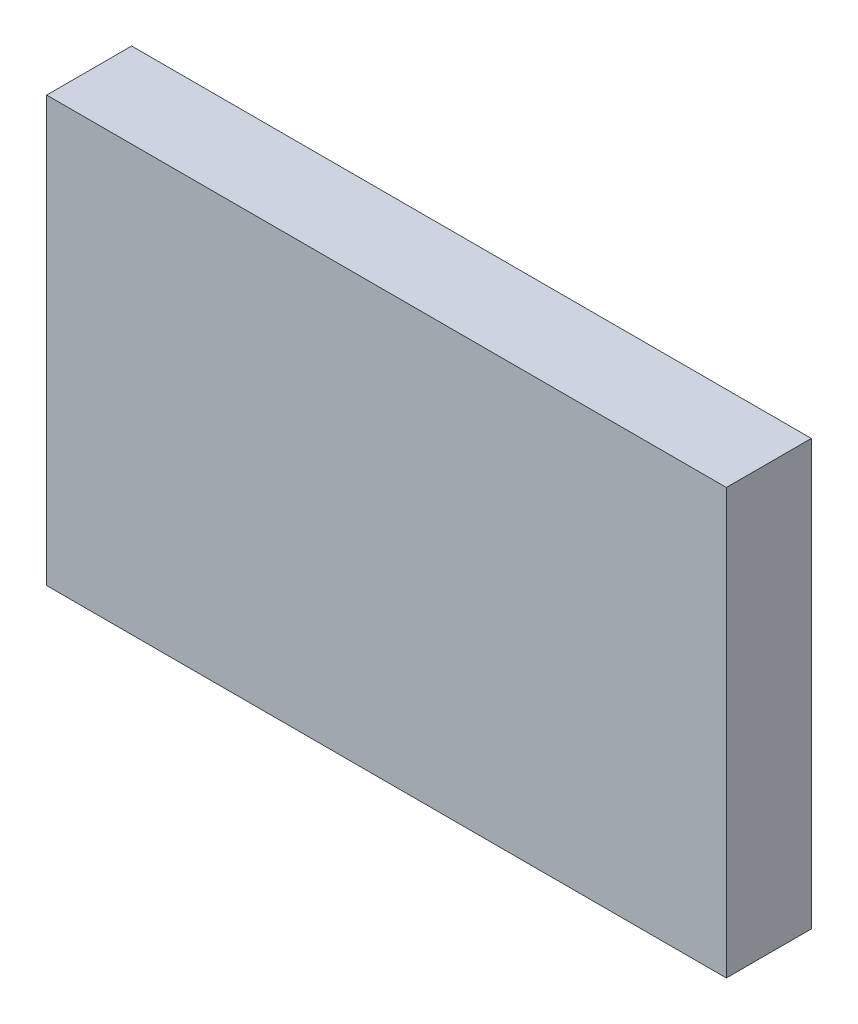
SolidWorks part; units mm, degrees
ref_plane "前视基准面" through (0, 0, 0) normal (0, 0, 1) x (1, 0, 0)
ref_plane "上视基准面" through (0, 0, 0) normal (0, 1, 0) x (1, 0, 0)
ref_plane "右视基准面" through (0, 0, 0) normal (1, 0, 0) x (0, 0, -1)
sketch "base" plane through (0, 0, 0) normal (0, 0, 1) x (1, 0, 0)
  line L1 (-40, -25) -> (40, -25)
  line L2 (-40, -25) -> (-40, 25)
  line L3 (-40, 25) -> (40, 25)
  line L4 (40, -25) -> (40, 25)
  line L5 (-40, -25) -> (40, 25) construction
  line L6 (-40, 25) -> (40, -25) construction
  point P0 (0, 0)
  dimension "宽度_0" = 80
  dimension "高度_0" = 50
extrude "block" add sketch "base" along normal blind 10
